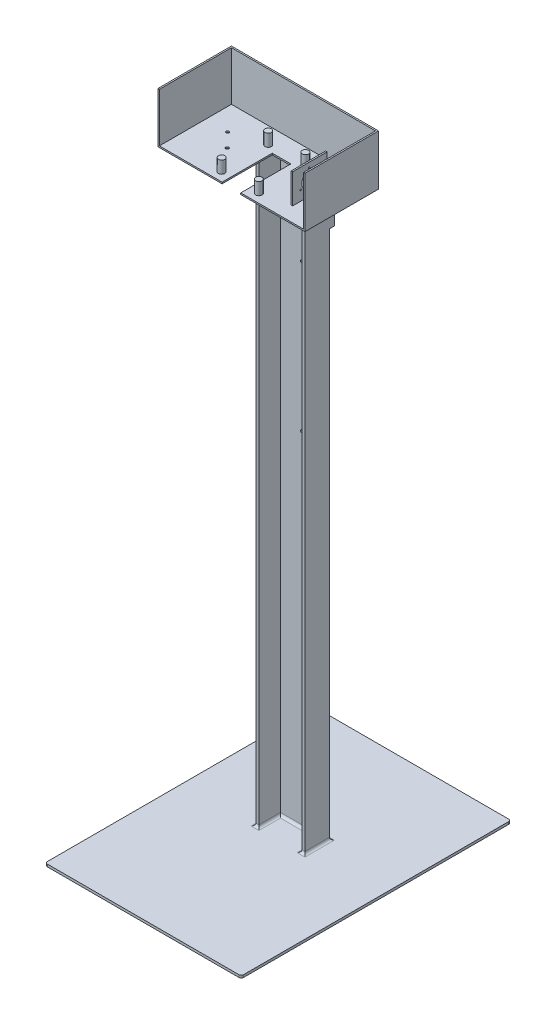
SolidWorks part; units mm, degrees
ref_plane "Front Plane" through (0, 0, 0) normal (0, 0, 1) x (1, 0, 0)
ref_plane "Top Plane" through (0, 0, 0) normal (0, 1, 0) x (1, 0, 0)
ref_plane "Right Plane" through (0, 0, 0) normal (1, 0, 0) x (0, 0, -1)
sketch "Sketch1" plane through (0, 0, 0) normal (0, 1, 0) x (1, 0, 0)
  line L1 (0, 0) -> (400, 0)
  line L2 (0, 0) -> (0, -550)
  line L3 (0, -550) -> (400, -550)
  line L4 (400, 0) -> (400, -550)
  dimension "D1" = 400
  dimension "D2" = 550
extrude "Boss-Extrude2" add sketch "Sketch1" along normal blind 5
sketch "Sketch2" plane through (0, 5, 0) normal (0, 1, 0) x (1, 0, 0)
  line L0 (150, -270) -> (150, -220)
  line L1 (150, -220) -> (250, -220)
  line L2 (250, -220) -> (250, -270)
  line L4 (0, 0) -> (0, -550) construction
  line L5 (400, 0) -> (0, 0) construction
  dimension "D1" = 100
  dimension "D2" = 50
  dimension "D3" = 50
  dimension "D4" = 150
  dimension "D5" = 220
extrude "Extrude-Thin1" add sketch "Sketch2" along normal blind 1200 thin
fillet "Fillet3" radius 5 12 edges at (153, 5, 270) (156, 5, 248) (200, 5, 226) (244, 5, 248) (247, 5, 270) (0, 2.5, 550) (150, 5, 245) (0, 2.5, 0) (400, 2.5, 550) (400, 2.5, 0) (250, 5, 245) (200, 5, 220)
sketch "Sketch7" plane through (0, 1205, 0) normal (0, 1, 0) x (1, 0, 0)
  line L0 (145, -215) -> (255, -215) construction
  line L1 (350, -220) -> (50, -220)
  line L2 (350, -220) -> (350, -370)
  line L3 (350, -370) -> (219, -370)
  line L4 (50, -220) -> (50, -370)
  line L5 (250, -220) -> (250, -270) construction
  line L7 (150, -270) -> (150, -220) construction
  line L11 (219, -370) -> (219, -267.7197)
  line L13 (219, -267.7197) -> (181, -267.7197)
  line L15 (181, -267.7197) -> (181, -370)
  line L16 (156, -270) -> (156, -226) construction
  line L17 (244, -226) -> (244, -270) construction
  line L18 (150, -220) -> (250, -220) construction
  line L19 (181, -370) -> (50, -370)
  point P18 (200, -220)
  dimension "D1" = 5
  dimension "D2" = 100
  dimension "D3" = 100
  dimension "D4" = 150
  dimension "D5" = 25
  dimension "D6" = 25
  dimension "D7" = 47.7197
extrude "Boss-Extrude4" add sketch "Sketch7" along normal blind 3 contours L2 L3 L11 L13 L15 L19 L4 L1
sketch "Sketch8" plane through (0, 1208, 0) normal (0, 1, 0) x (1, 0, 0)
  line L1 (295, -270) -> (292, -270)
  line L2 (295, -270) -> (295, -340)
  line L4 (292, -270) -> (292, -340)
  line L5 (219, -370) -> (219, -267.7197) construction
  line L6 (295, -340) -> (292, -340)
  line L7 (350, -370) -> (219, -370) construction
  point P5 (293.5, -270)
  dimension "D1" = 76
  dimension "D2" = 3
  dimension "D3" = 100
  dimension "D4" = 30
extrude "Boss-Extrude5" add sketch "Sketch8" along normal blind 60.4
sketch "Sketch9" plane through (295, 0, 0) normal (1, 0, 0) x (0, 0, -1)
  line L1 (-340, 1208) -> (-270, 1208) construction
  line L2 (-270, 1268.4) -> (-270, 1208) construction
  circle A0 centre (-306.55, 1238.2) radius 15
  dimension "D2" = 30.2
  dimension "D3" = 30
  dimension "D1" = 36.55
extrude "Cut-Extrude2" cut sketch "Sketch9" against normal blind 3
sketch "Sketch10" plane through (292, 0, 0) normal (-1, 0, 0) x (0, 0, 1)
  circle A0 centre (306.55, 1238.2) radius 20 construction
  circle A1 centre (306.55, 1258.2) radius 1.5
  circle A2 centre (289.2295, 1228.2) radius 1.5
  circle A3 centre (323.8705, 1228.2) radius 1.5
  circle A4 centre (306.55, 1238.2) radius 15 construction
  dimension "D1" = 40
  dimension "D2" = 120
  dimension "D3" = 120
  dimension "D4" = 3
  dimension "D5" = 3
  dimension "D6" = 3
extrude "Cut-Extrude3" cut sketch "Sketch10" against normal blind 3
sketch "Sketch12" plane through (0, 1208, 0) normal (0, 1, 0) x (1, 0, 0)
  line L0 (350, -370) -> (219, -370) construction
  line L1 (181, -370) -> (50, -370) construction
  line L2 (219, -370) -> (219, -267.7197) construction
  line L3 (181, -267.7197) -> (181, -370) construction
  circle A0 centre (162, -352) radius 6.5
  circle A1 centre (162, -257) radius 6.5
  circle A2 centre (238, -257) radius 6.5
  circle A3 centre (238, -352) radius 6.5
  dimension "D1" = 13
  dimension "D2" = 13
  dimension "D3" = 13
  dimension "D4" = 13
  dimension "D5" = 95
  dimension "D6" = 95
  dimension "D7" = 18
  dimension "D8" = 18
  dimension "D10" = 19
  dimension "D11" = 19
  dimension "D12" = 19
  dimension "D9" = 19
extrude "Boss-Extrude6" add sketch "Sketch12" along normal blind 25
sketch "Sketch13" plane through (0, 1208, 0) normal (0, 1, 0) x (1, 0, 0)
  circle A0 centre (126, -304.5) radius 3
  circle A1 centre (98.0935, -275.8429) radius 3
  circle A3 centre (162, -352) radius 6.5 construction
  circle A4 centre (162, -352) radius 6.5 construction
  dimension "D1" = 6
  dimension "D2" = 6
  dimension "D4" = 47.5
  dimension "D5" = 36
  dimension "D3" = 40
extrude "Cut-Extrude5" cut sketch "Sketch13" against normal blind 3
sketch "Sketch15" plane through (0, 1208, 0) normal (0, 1, 0) x (1, 0, 0)
  line L0 (350, -370) -> (350, -220)
  line L1 (350, -220) -> (50, -220)
  line L2 (50, -220) -> (50, -370)
  line L3 (350, -220) -> (50, -220) construction
  line L4 (350, -220) -> (350, -370) construction
  line L5 (50, -220) -> (50, -370) construction
  dimension "D1" = 0
  dimension "D2" = 0
  dimension "D3" = 0
extrude "Extrude-Thin2" add sketch "Sketch15" along normal blind 100 thin thin type one direction reverse wall 3
hole_wizard "Ø6.0mm Dowel Hole1" positions "Sketch16" profile "Sketch17" hole size "Ø6.0" standard "BSI" end condition through all
sketch "Sketch16" plane through (0, 0, 220) normal (0, 0, -1) x (-1, 0, 0)
  line L0 (-150, 1205) -> (-150, 10) construction
  line L1 (-150, 1205) -> (-50, 1205) construction
  line L2 (-250, 1205) -> (-250, 10) construction
  point P0 (-200, 1005)
  point P2 (-200, 705)
  dimension "D1" = 50
  dimension "D2" = 300
  dimension "D3" = 200
  dimension "D4" = 50
sketch "Sketch17" plane through (200, 1005, 220) normal (1, 0, 0) x (0, 1, 0)
  line L0 (0, 0) -> (0, 330)
  line L1 (0, 330) -> (3, 330)
  line L2 (3, 330) -> (3, 0)
  line L5 (3, 0) -> (0, 0)
  line L11 (0, -6.35) -> (0, 107.95) construction
  dimension "Thru Hole Dia." = 6
  dimension "Thru Hole Depth" = 330
sketch "Sketch18" plane through (0, 0, 220) normal (0, 0, -1) x (-1, 0, 0)
  line L0 (-150, 1205) -> (-150, 10) construction
  line L1 (-250, 1205) -> (-150, 1205)
  line L2 (-250, 1205) -> (-250, 1165)
  line L3 (-250, 1165) -> (-150, 1165)
  line L4 (-150, 1205) -> (-150, 1165)
  line L5 (-250, 1205) -> (-250, 10) construction
  line L6 (-250, 1125) -> (-150, 1125)
  line L7 (-250, 1125) -> (-250, 1085)
  line L8 (-250, 1085) -> (-150, 1085)
  line L9 (-150, 1125) -> (-150, 1085)
  dimension "D1" = 40
  dimension "D2" = 40
  dimension "D3" = 40
extrude "Boss-Extrude7" add sketch "Sketch18" along normal blind 10
hole_wizard "Ø6.0mm Dowel Hole2" positions "Sketch19" profile "Sketch20" hole size "Ø6.0" standard "BSI" end condition through all
sketch "Sketch19" plane through (0, 0, 210) normal (0, 0, -1) x (-1, 0, 0)
  line L0 (-250, 1205) -> (-250, 1165) construction
  line L1 (-350, 1205) -> (-250, 1205) construction
  line L2 (-250, 1125) -> (-250, 1085) construction
  line L3 (-250, 1165) -> (-150, 1165) construction
  line L5 (-250, 1085) -> (-150, 1085) construction
  point P0 (-225, 1185)
  point P2 (-175, 1185)
  point P4 (-175, 1105)
  point P6 (-225, 1105)
  dimension "D1" = 25
  dimension "D2" = 50
  dimension "D3" = 20
  dimension "D4" = 50
  dimension "D5" = 25
  dimension "D6" = 80
  dimension "D7" = 20
  dimension "D8" = 20
sketch "Sketch20" plane through (225, 1185, 210) normal (1, 0, 0) x (0, 1, 0)
  line L0 (0, 0) -> (0, 340)
  line L1 (0, 340) -> (3, 340)
  line L2 (3, 340) -> (3, 0)
  line L5 (3, 0) -> (0, 0)
  line L11 (0, -6.35) -> (0, 107.95) construction
  dimension "Thru Hole Dia." = 6
  dimension "Thru Hole Depth" = 340
